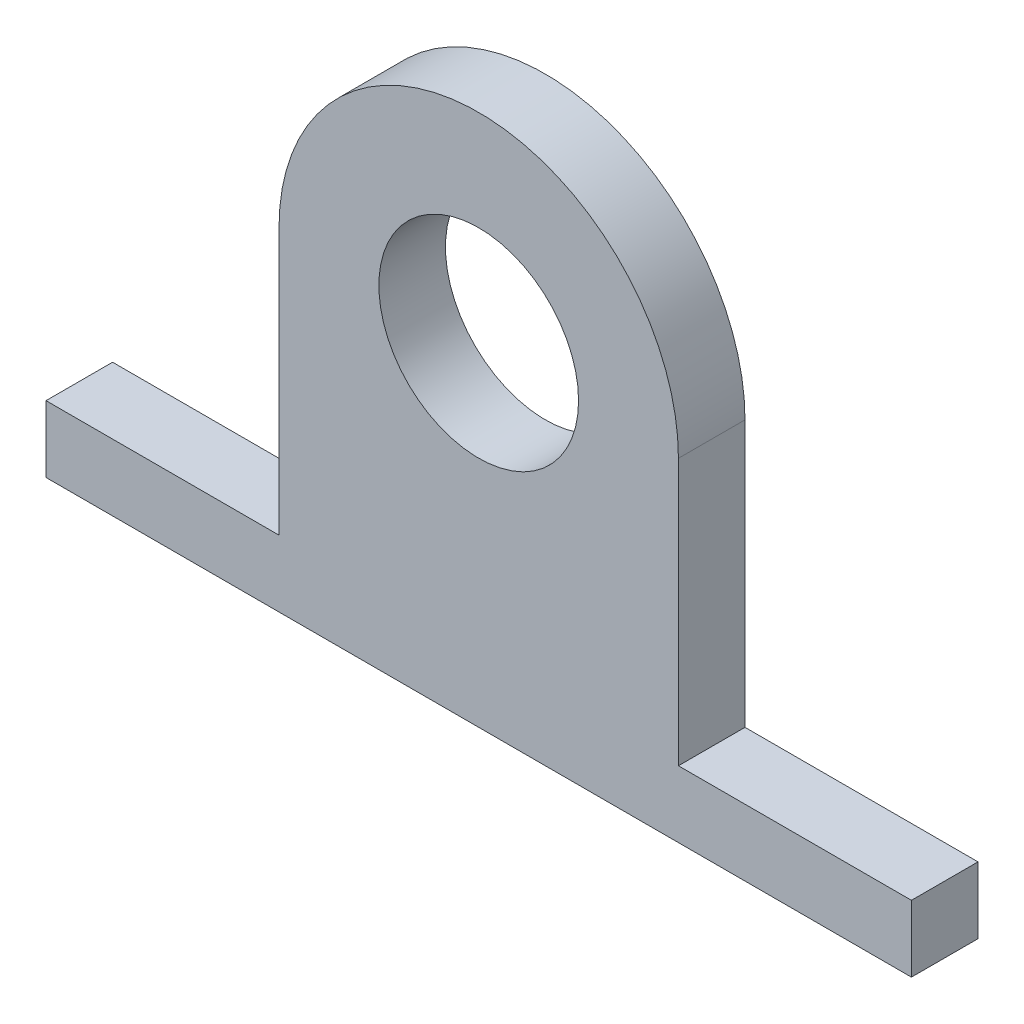
SolidWorks part; units mm, degrees
ref_plane "Plan de face" through (0, 0, 0) normal (0, 0, 1) x (1, 0, 0)
ref_plane "Plan de dessus" through (0, 0, 0) normal (0, 1, 0) x (1, 0, 0)
ref_plane "Plan de droite" through (0, 0, 0) normal (1, 0, 0) x (0, 0, -1)
sketch "Esquisse1" plane through (0, 0, 0) normal (0, 0, 1) x (1, 0, 0)
  line L0 (-65, 0) -> (65, 0)
  line L1 (65, 0) -> (65, 10)
  line L2 (65, 10) -> (30, 10)
  line L3 (30, 10) -> (30, 50)
  line L4 (0, 0) -> (0, 180.6205) construction
  line L6 (-65, 0) -> (-65, 10)
  line L7 (-65, 10) -> (-30, 10)
  line L8 (-30, 10) -> (-30, 50)
  line L9 (-30, -8.362) -> (-30, 88.0944) construction
  line L10 (30, -8.362) -> (30, 94.138) construction
  arc A0 (30, 50) -> (-30, 50) centre (0, 50) ccw
  circle A1 centre (0, 50) radius 15
  point P8 (0, 0)
  dimension "D3" = 30
  dimension "D4" = 30
  dimension "D1" = 130
  dimension "D2" = 10
  dimension "D5" = 50
extrude "Boss.-Extru.1" add sketch "Esquisse1" along normal blind 10
sketch "Esquisse2" plane through (0, 0, 10) normal (0, 0, 1) x (1, 0, 0)
  line L0 (-30, 10) -> (-30, 0) construction
  line L2 (-45.8664, -4.4721) -> (-34, -4.4721) construction
  line L7 (-45.8664, 1.5279) -> (-34, 1.5279)
  line L8 (-45.8664, -10.4721) -> (-34, -10.4721)
  line L9 (-65, 0) -> (65, 0) construction
  line L10 (-34, 1.5279) -> (-34, 0) construction
  arc A4 (-45.8664, 1.5279) -> (-45.8664, -10.4721) centre (-45.8664, -4.4721) ccw
  arc A5 (-34, -10.4721) -> (-34, 1.5279) centre (-34, -4.4721) ccw
  point P5 (-39.9332, -4.4721)
  point P14 (-30.0389, 0)
  point P15 (0, 0)
  dimension "D2" = 4
  dimension "D1" = 6
